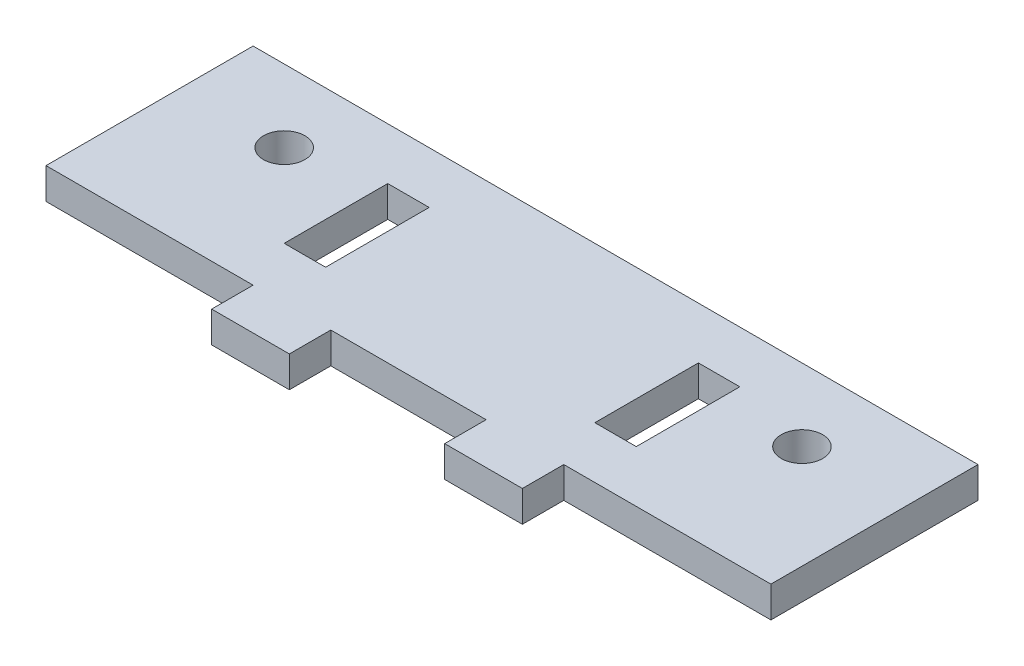
SolidWorks part; units mm, degrees
ref_plane "Front Plane" through (0, 0, 0) normal (0, 0, 1) x (1, 0, 0)
ref_plane "Top Plane" through (0, 0, 0) normal (0, 1, 0) x (1, 0, 0)
ref_plane "Right Plane" through (0, 0, 0) normal (1, 0, 0) x (0, 0, -1)
sketch "Sketch1" plane through (0, 0, 0) normal (0, 1, 0) x (1, 0, 0)
  line L0 (20, 20) -> (20, 0) construction
  line L1 (0, 0) -> (20, 0)
  line L2 (0, 0) -> (0, 20)
  line L3 (0, 20) -> (70, 20)
  line L4 (70, 0) -> (70, 20)
  line L5 (50, 20) -> (50, 0) construction
  line L6 (35, 20) -> (35, 0) construction
  line L7 (18, 15) -> (22, 15)
  line L8 (18, 15) -> (18, 5)
  line L9 (18, 5) -> (22, 5)
  line L10 (22, 15) -> (22, 5)
  line L11 (52, 5) -> (48, 5)
  line L12 (48, 15) -> (48, 5)
  line L13 (52, 15) -> (52, 5)
  line L14 (52, 15) -> (48, 15)
  line L15 (10, 20) -> (10, 0) construction
  line L16 (50, -4) -> (42.5, -4)
  line L17 (27.5, 0) -> (27.5, 20) construction
  line L18 (42.5, 0) -> (42.5, -4)
  line L20 (20, 0) -> (20, -4)
  line L21 (20, -4) -> (27.5, -4)
  line L22 (27.5, 0) -> (27.5, -4)
  line L24 (50, 0) -> (50, -4)
  line L25 (27.5, 0) -> (42.5, 0)
  line L26 (50, 0) -> (70, 0)
  circle A0 centre (10, 13) radius 2
  circle A2 centre (60, 13) radius 2
  dimension "D10" = 7.5
  dimension "D11" = 4
  dimension "D13" = 4
  dimension "D1" = 70
  dimension "D2" = 20
  dimension "D3" = 20
  dimension "D5" = 4
  dimension "D6" = 10
  dimension "D7" = 2
  dimension "D8" = 5
  dimension "D9" = 10
extrude "Boss-Extrude1" add sketch "Sketch1" along normal blind 3
